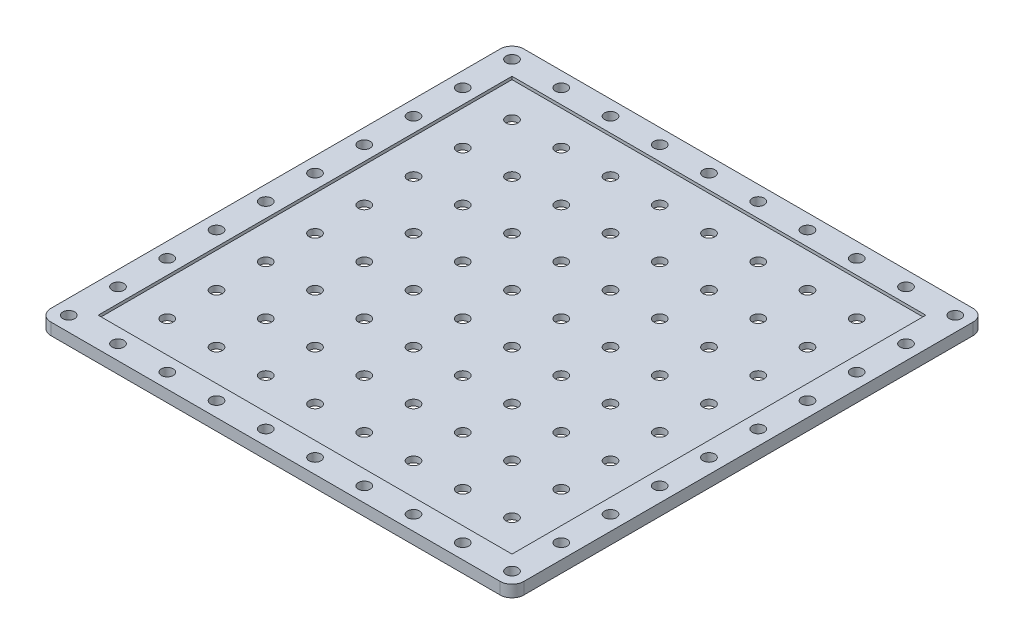
SolidWorks part; units mm, degrees
material "6061 Alloy"
ref_plane "Front Plane" through (0, 0, 0) normal (0, 0, 1) x (1, 0, 0)
ref_plane "Top Plane" through (0, 0, 0) normal (0, 1, 0) x (1, 0, 0)
ref_plane "Right Plane" through (0, 0, 0) normal (1, 0, 0) x (0, 0, -1)
sketch "Sketch1" plane through (0, 0, 0) normal (0, 1, 0) x (1, 0, 0)
  line L1 (40, 40) -> (-40, 40)
  line L2 (40, 40) -> (40, -40)
  line L3 (40, -40) -> (-40, -40)
  line L4 (-40, 40) -> (-40, -40)
  line L5 (40, 40) -> (-40, -40) construction
  line L6 (40, -40) -> (-40, 40) construction
  point P0 (0, 0)
extrude "Boss-Extrude1" add sketch "Sketch1" along normal blind 2
fillet "Fillet1" radius 2 4 edges at (-40, 1, -40) (40, 1, -40) (-40, 1, 40) (40, 1, 40)
sketch "Sketch3" plane through (0, 2, 0) normal (0, 1, 0) x (1, 0, 0)
  line L1 (-35, -35) -> (35, -35)
  line L2 (-35, -35) -> (-35, 35)
  line L3 (-35, 35) -> (35, 35)
  line L4 (35, -35) -> (35, 35)
  line L5 (-35, -35) -> (35, 35) construction
  line L6 (-35, 35) -> (35, -35) construction
  point P0 (0, 0)
extrude "Cut-Extrude2" cut sketch "Sketch3" against normal blind 0.5
sketch "Sketch4" plane through (0, 0, 0) normal (0, -1, 0) x (1, 0, 0)
  line L4 (35, -35) -> (35, 35)
  line L5 (-35, -35) -> (35, -35)
  line L6 (-35, 35) -> (-35, -35)
  line L7 (35, 35) -> (-35, 35)
  line L8 (35, -35) -> (35, 35)
  line L9 (-35, -35) -> (35, -35)
  line L10 (-35, 35) -> (-35, -35)
  line L11 (35, 35) -> (-35, 35)
  dimension "D1" = 0
extrude "Cut-Extrude3" cut sketch "Sketch4" against normal blind 0.5
sketch "Sketch5" plane through (0, 2, 0) normal (0, 1, 0) x (1, 0, 0)
  circle A0 centre (37.5, -37.5) radius 1
  circle A1 centre (29.17, -37.5) radius 1
  circle A2 centre (20.84, -37.5) radius 1
  circle A3 centre (12.51, -37.5) radius 1
  circle A4 centre (4.18, -37.5) radius 1
  circle A5 centre (-4.15, -37.5) radius 1
  circle A6 centre (-12.48, -37.5) radius 1
  circle A7 centre (-20.81, -37.5) radius 1
  circle A8 centre (-29.14, -37.5) radius 1
  circle A9 centre (-37.47, -37.5) radius 1
  circle A10 centre (29.17, -29.17) radius 1
  circle A11 centre (20.84, -29.17) radius 1
  circle A12 centre (12.51, -29.17) radius 1
  circle A13 centre (4.18, -29.17) radius 1
  circle A14 centre (-4.15, -29.17) radius 1
  circle A15 centre (-12.48, -29.17) radius 1
  circle A16 centre (-20.81, -29.17) radius 1
  circle A17 centre (-29.14, -29.17) radius 1
  circle A18 centre (-37.47, -29.17) radius 1
  circle A19 centre (29.17, -20.84) radius 1
  circle A20 centre (20.84, -20.84) radius 1
  circle A21 centre (12.51, -20.84) radius 1
  circle A22 centre (4.18, -20.84) radius 1
  circle A23 centre (-4.15, -20.84) radius 1
  circle A24 centre (-12.48, -20.84) radius 1
  circle A25 centre (-20.81, -20.84) radius 1
  circle A26 centre (-29.14, -20.84) radius 1
  circle A27 centre (-37.47, -20.84) radius 1
  circle A28 centre (29.17, -12.51) radius 1
  circle A29 centre (20.84, -12.51) radius 1
  circle A30 centre (12.51, -12.51) radius 1
  circle A31 centre (4.18, -12.51) radius 1
  circle A32 centre (-4.15, -12.51) radius 1
  circle A33 centre (-12.48, -12.51) radius 1
  circle A34 centre (-20.81, -12.51) radius 1
  circle A35 centre (-29.14, -12.51) radius 1
  circle A36 centre (-37.47, -12.51) radius 1
  circle A37 centre (29.17, -4.18) radius 1
  circle A38 centre (20.84, -4.18) radius 1
  circle A39 centre (12.51, -4.18) radius 1
  circle A40 centre (4.18, -4.18) radius 1
  circle A41 centre (-4.15, -4.18) radius 1
  circle A42 centre (-12.48, -4.18) radius 1
  circle A43 centre (-20.81, -4.18) radius 1
  circle A44 centre (-29.14, -4.18) radius 1
  circle A45 centre (-37.47, -4.18) radius 1
  circle A46 centre (29.17, 4.15) radius 1
  circle A47 centre (20.84, 4.15) radius 1
  circle A48 centre (12.51, 4.15) radius 1
  circle A49 centre (4.18, 4.15) radius 1
  circle A50 centre (-4.15, 4.15) radius 1
  circle A51 centre (-12.48, 4.15) radius 1
  circle A52 centre (-20.81, 4.15) radius 1
  circle A53 centre (-29.14, 4.15) radius 1
  circle A54 centre (-37.47, 4.15) radius 1
  circle A55 centre (29.17, 12.48) radius 1
  circle A56 centre (20.84, 12.48) radius 1
  circle A57 centre (12.51, 12.48) radius 1
  circle A58 centre (4.18, 12.48) radius 1
  circle A59 centre (-4.15, 12.48) radius 1
  circle A60 centre (-12.48, 12.48) radius 1
  circle A61 centre (-20.81, 12.48) radius 1
  circle A62 centre (-29.14, 12.48) radius 1
  circle A63 centre (-37.47, 12.48) radius 1
  circle A64 centre (29.17, 20.81) radius 1
  circle A65 centre (20.84, 20.81) radius 1
  circle A66 centre (12.51, 20.81) radius 1
  circle A67 centre (4.18, 20.81) radius 1
  circle A68 centre (-4.15, 20.81) radius 1
  circle A69 centre (-12.48, 20.81) radius 1
  circle A70 centre (-20.81, 20.81) radius 1
  circle A71 centre (-29.14, 20.81) radius 1
  circle A72 centre (-37.47, 20.81) radius 1
  circle A73 centre (29.17, 29.14) radius 1
  circle A74 centre (20.84, 29.14) radius 1
  circle A75 centre (12.51, 29.14) radius 1
  circle A76 centre (4.18, 29.14) radius 1
  circle A77 centre (-4.15, 29.14) radius 1
  circle A78 centre (-12.48, 29.14) radius 1
  circle A79 centre (-20.81, 29.14) radius 1
  circle A80 centre (-29.14, 29.14) radius 1
  circle A81 centre (-37.47, 29.14) radius 1
  circle A82 centre (29.17, 37.47) radius 1
  circle A83 centre (20.84, 37.47) radius 1
  circle A84 centre (12.51, 37.47) radius 1
  circle A85 centre (4.18, 37.47) radius 1
  circle A86 centre (-4.15, 37.47) radius 1
  circle A87 centre (-12.48, 37.47) radius 1
  circle A88 centre (-20.81, 37.47) radius 1
  circle A89 centre (-29.14, 37.47) radius 1
  circle A90 centre (-37.47, 37.47) radius 1
  circle A91 centre (37.5, -29.17) radius 1
  circle A92 centre (37.5, -20.84) radius 1
  circle A93 centre (37.5, -12.51) radius 1
  circle A94 centre (37.5, -4.18) radius 1
  circle A95 centre (37.5, 4.15) radius 1
  circle A96 centre (37.5, 12.48) radius 1
  circle A97 centre (37.5, 20.81) radius 1
  circle A98 centre (37.5, 29.14) radius 1
  circle A99 centre (37.5, 37.47) radius 1
  point P0 (0, 0)
  dimension "D1" = 2
  dimension "D2" = 10
  dimension "D3" = 10
extrude "Cut-Extrude4" cut sketch "Sketch5" against normal blind 10
